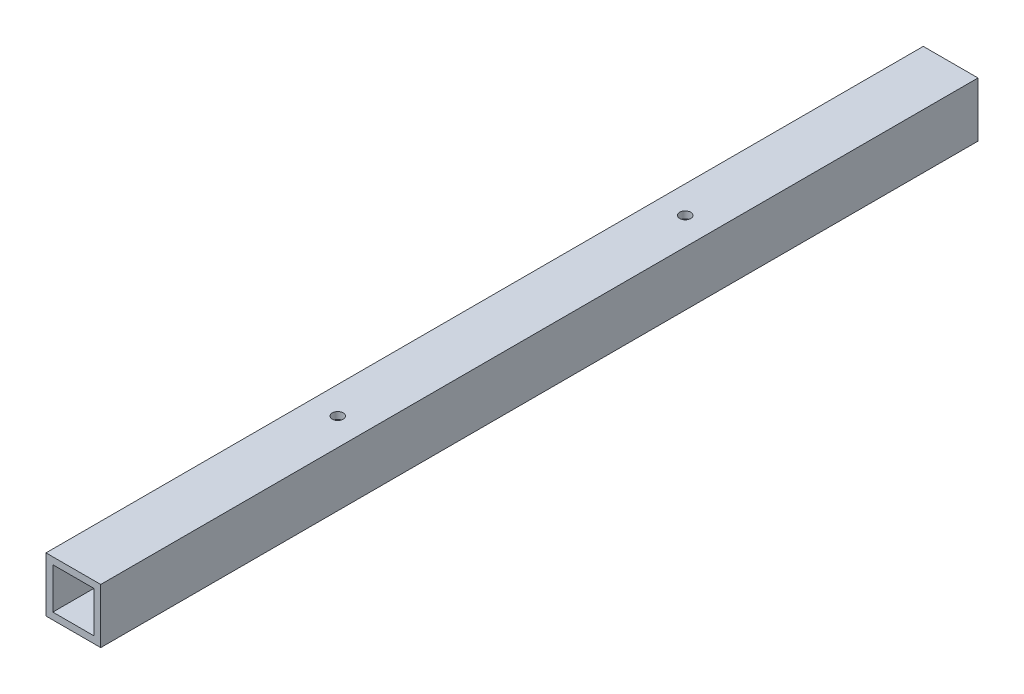
SolidWorks part; units mm, degrees
material "6061 Alloy"
ref_plane "Front" through (0, 0, 0) normal (0, 0, 1) x (1, 0, 0)
ref_plane "Top" through (0, 0, 0) normal (0, 1, 0) x (1, 0, 0)
ref_plane "Right" through (0, 0, 0) normal (1, 0, 0) x (0, 0, -1)
sketch "Sketch1" plane through (0, 0, 0) normal (0, 0, 1) x (1, 0, 0)
  line L1 (-12.7, 12.7) -> (12.7, 12.7)
  line L2 (-12.7, 12.7) -> (-12.7, -12.7)
  line L3 (-12.7, -12.7) -> (12.7, -12.7)
  line L4 (12.7, 12.7) -> (12.7, -12.7)
  line L5 (-12.7, 12.7) -> (12.7, -12.7) construction
  line L6 (-12.7, -12.7) -> (12.7, 12.7) construction
  line L7 (-9.525, 9.525) -> (9.525, 9.525)
  line L8 (-9.525, 9.525) -> (-9.525, -9.525)
  line L9 (-9.525, -9.525) -> (9.525, -9.525)
  line L10 (9.525, 9.525) -> (9.525, -9.525)
  line L11 (-9.525, 9.525) -> (9.525, -9.525) construction
  line L12 (-9.525, -9.525) -> (9.525, 9.525) construction
  point P0 (0, 0)
  point P6 (0, 0)
  dimension "D1" = 25.4
  dimension "D2" = 3.175
extrude "Boss-Extrude1" add sketch "Sketch1" along normal blind 407.1937
hole_wizard "#10 Clearance Hole1" positions "Sketch2" profile "Sketch3" hole size "#10" standard "ANSI Inch" end condition through all
sketch "Sketch2" plane through (146.05, 12.7, 546.735) normal (0, 1, 0) x (0, 0, 1)
  point P0 (-423.545, -146.05)
  point P3 (-262.255, -146.05)
sketch "Sketch3" plane through (0, 12.7, 123.19) normal (1, 0, 0) x (0, 0, 1)
  line L0 (0, 0) -> (0, 25.4)
  line L1 (0, 25.4) -> (2.5527, 25.4)
  line L2 (2.5527, 25.4) -> (2.5527, 0)
  line L3 (2.5527, 0) -> (0, 0)
  line L4 (0, -6.35) -> (0, 107.95) construction
  dimension "Thru Hole Dia." = 5.1054
  dimension "Thru Hole Depth" = 25.4
sketch "Sketch4" plane through (0, -12.7, 0) normal (0, 1, 0) x (1, 0, 0)
  circle A0 centre (0, -123.19) radius 7.62
  circle A1 centre (0, -284.48) radius 7.62
  circle A2 centre (0, -284.48) radius 2.5527 construction
  dimension "D1" = 15.24
  dimension "D2" = 15.24
extrude "Cut-Extrude1" cut sketch "Sketch4" along normal up to next
